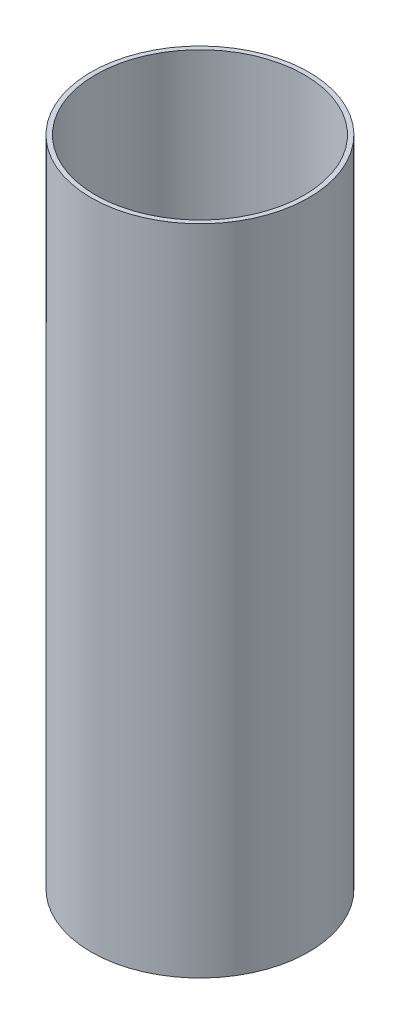
SolidWorks part; units mm, degrees
ref_plane "Front Plane" through (0, 0, 0) normal (0, 0, 1) x (1, 0, 0)
ref_plane "Top Plane" through (0, 0, 0) normal (0, 1, 0) x (1, 0, 0)
ref_plane "Right Plane" through (0, 0, 0) normal (1, 0, 0) x (0, 0, -1)
sketch "Sketch1" plane through (0, 0, 0) normal (0, 1, 0) x (1, 0, 0)
  circle A0 centre (0, 0) radius 73.025
  circle A1 centre (0, 0) radius 76.2
  circle A2 centre (0, 0) radius 76.2
  dimension "D2" = 152.4
  dimension "D3" = 146.05
extrude "Boss-Extrude1" add sketch "Sketch1" along normal blind 457.2 contours A0 | A1
